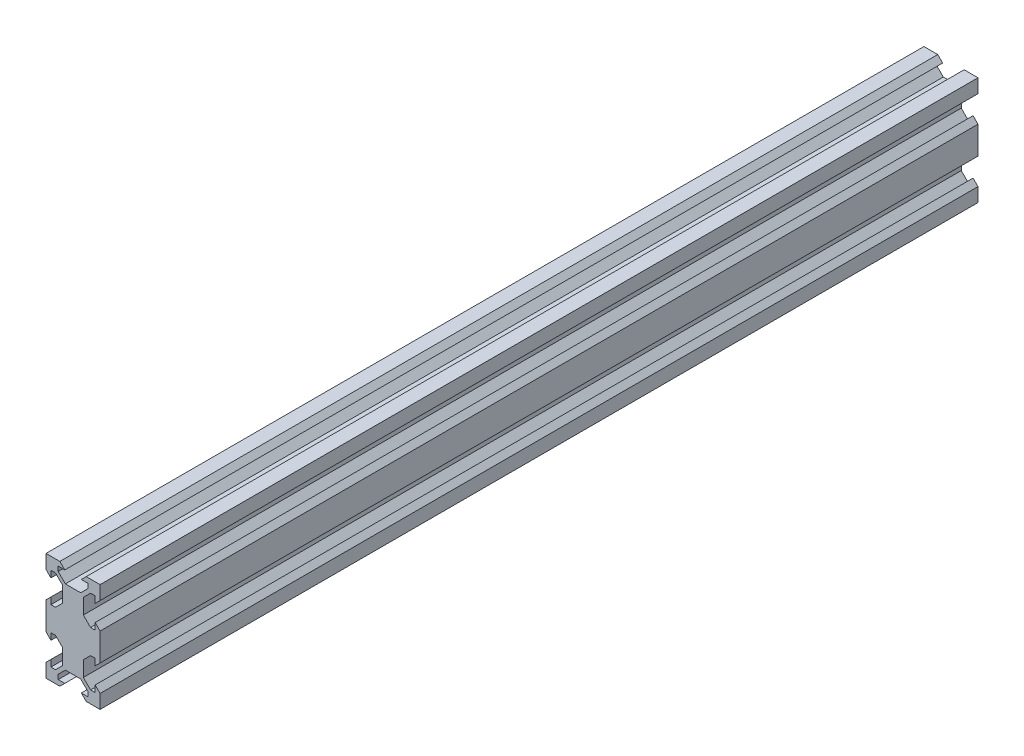
SolidWorks part; units mm, degrees
ref_plane "Front Plane" through (0, 0, 0) normal (0, 0, 1) x (1, 0, 0)
ref_plane "Top Plane" through (0, 0, 0) normal (0, 1, 0) x (1, 0, 0)
ref_plane "Right Plane" through (0, 0, 0) normal (1, 0, 0) x (0, 0, -1)
sketch "Sketch1" plane through (0, 0, 0) normal (0, 0, 1) x (1, 0, 0)
  line L1 (0, 0) -> (20, 0)
  line L2 (0, 0) -> (0, 40)
  line L3 (0, 40) -> (20, 40)
  line L4 (20, 0) -> (20, 40)
  line L5 (0, 0) -> (20, 40) construction
  line L6 (0, 40) -> (20, 0) construction
  point P4 (10, 20)
  dimension "D1" = 20
  dimension "D2" = 40
extrude "Boss-Extrude1" add sketch "Sketch1" along normal blind 324.8
sketch "Sketch2" plane through (0, 0, 324.8) normal (0, 0, 1) x (1, 0, 0)
  line L0 (5.12, 40) -> (6.94, 38.18)
  line L1 (20, 40) -> (0, 40) construction
  line L3 (13.06, 38.18) -> (14.88, 40)
  line L4 (0, 40) -> (20, 40) construction
  line L5 (20, 40) -> (10, 40) construction
  line L6 (10, 40) -> (10, 38.18) construction
  line L7 (5.12, 40) -> (14.88, 40)
  line L8 (6.94, 38.18) -> (4.5, 38.18)
  line L9 (4.5, 38.18) -> (4.5, 36.4758)
  line L10 (4.5, 36.4758) -> (7.1658, 33.81)
  line L11 (7.1658, 33.81) -> (12.8342, 33.81)
  line L12 (12.8342, 33.81) -> (15.5, 36.4758)
  line L13 (15.5, 36.4758) -> (15.5, 38.18)
  line L14 (15.5, 38.18) -> (13.06, 38.18)
  line L15 (20, 40) -> (0, 20) construction
  line L16 (0, 40) -> (0, 0) construction
  line L17 (20, 30) -> (18.18, 30) construction
  line L18 (18.18, 35.5) -> (18.18, 33.06)
  line L19 (16.4758, 35.5) -> (18.18, 35.5)
  line L20 (13.81, 32.8342) -> (16.4758, 35.5)
  line L21 (13.81, 27.1658) -> (13.81, 32.8342)
  line L22 (16.4758, 24.5) -> (13.81, 27.1658)
  line L23 (18.18, 24.5) -> (16.4758, 24.5)
  line L24 (18.18, 26.94) -> (18.18, 24.5)
  line L25 (20, 25.12) -> (20, 34.88)
  line L26 (18.18, 33.06) -> (20, 34.88)
  line L28 (20, 25.12) -> (18.18, 26.94)
  line L29 (0, 20) -> (20, 20) construction
  line L30 (20, 0) -> (20, 40) construction
  line L31 (20, 10) -> (18.18, 10) construction
  line L32 (10, 0) -> (10, 1.82) construction
  line L33 (20, 0) -> (10, 0) construction
  line L34 (20, 14.88) -> (18.18, 13.06)
  line L36 (18.18, 6.94) -> (20, 5.12)
  line L37 (20, 14.88) -> (20, 5.12)
  line L38 (18.18, 13.06) -> (18.18, 15.5)
  line L39 (18.18, 15.5) -> (16.4758, 15.5)
  line L40 (16.4758, 15.5) -> (13.81, 12.8342)
  line L41 (13.81, 12.8342) -> (13.81, 7.1658)
  line L42 (13.81, 7.1658) -> (16.4758, 4.5)
  line L43 (16.4758, 4.5) -> (18.18, 4.5)
  line L44 (18.18, 4.5) -> (18.18, 6.94)
  line L45 (15.5, 1.82) -> (13.06, 1.82)
  line L46 (15.5, 3.5242) -> (15.5, 1.82)
  line L47 (12.8342, 6.19) -> (15.5, 3.5242)
  line L48 (7.1658, 6.19) -> (12.8342, 6.19)
  line L49 (4.5, 3.5242) -> (7.1658, 6.19)
  line L50 (4.5, 1.82) -> (4.5, 3.5242)
  line L51 (6.94, 1.82) -> (4.5, 1.82)
  line L52 (5.12, 0) -> (14.88, 0)
  line L53 (13.06, 1.82) -> (14.88, 0)
  line L55 (5.12, 0) -> (6.94, 1.82)
  line L56 (10, 40) -> (10, 0) construction
  line L57 (0, 10) -> (1.82, 10) construction
  line L58 (0, 30) -> (1.82, 30) construction
  line L59 (1.82, 4.5) -> (1.82, 6.94)
  line L60 (3.5242, 4.5) -> (1.82, 4.5)
  line L61 (6.19, 7.1658) -> (3.5242, 4.5)
  line L62 (6.19, 12.8342) -> (6.19, 7.1658)
  line L63 (3.5242, 15.5) -> (6.19, 12.8342)
  line L64 (1.82, 15.5) -> (3.5242, 15.5)
  line L65 (1.82, 13.06) -> (1.82, 15.5)
  line L66 (0, 14.88) -> (0, 5.12)
  line L67 (1.82, 6.94) -> (0, 5.12)
  line L69 (0, 14.88) -> (1.82, 13.06)
  line L70 (0, 25.12) -> (1.82, 26.94)
  line L72 (1.82, 33.06) -> (0, 34.88)
  line L73 (0, 25.12) -> (0, 34.88)
  line L74 (1.82, 26.94) -> (1.82, 24.5)
  line L75 (1.82, 24.5) -> (3.5242, 24.5)
  line L76 (3.5242, 24.5) -> (6.19, 27.1658)
  line L77 (6.19, 27.1658) -> (6.19, 32.8342)
  line L78 (6.19, 32.8342) -> (3.5242, 35.5)
  line L79 (3.5242, 35.5) -> (1.82, 35.5)
  line L80 (1.82, 35.5) -> (1.82, 33.06)
  dimension "D1" = 90
  dimension "D3" = 6.12
  dimension "D5" = 11
  dimension "D6" = 6.19
  dimension "D7" = 1.38
extrude "Cut-Extrude1" cut sketch "Sketch2" against normal through all
